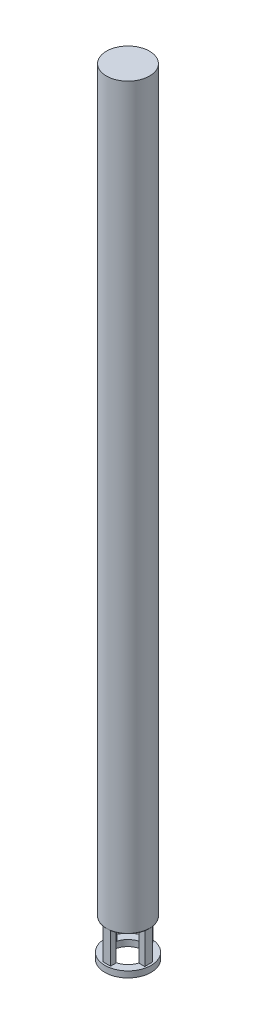
SolidWorks part; units mm, degrees
ref_plane "Plan de face" through (0, 0, 0) normal (0, 0, 1) x (1, 0, 0)
ref_plane "Plan de dessus" through (0, 0, 0) normal (0, 1, 0) x (1, 0, 0)
ref_plane "Plan de droite" through (0, 0, 0) normal (1, 0, 0) x (0, 0, -1)
sketch "Esquisse1" plane through (0, 0, 0) normal (0, 0, 1) x (1, 0, 0)
  line L0 (0, 0) -> (0, 90.4874) construction
  line L2 (0, 120) -> (-3.5, 120)
  line L3 (0, 120) -> (0, 0)
  line L4 (0, 0) -> (-3.5, 0)
  line L5 (-3.5, 120) -> (-3.5, 0)
  dimension "D1" = 120
  dimension "D2" = 3.5
revolve "Révolution1" add sketch "Esquisse1" angle 360 about L0
sketch "Esquisse6" plane through (0, 0, 0) normal (0, 1, 0) x (1, 0, 0)
  circle A1 centre (0, 0) radius 3.75
  circle A2 centre (0, 0) radius 2.5
  dimension "6" = 7.5
  dimension "D1" = 5
extrude "Boss.-Extru.2" add sketch "Esquisse6" along normal blind 1 from offset 6 offset against normal yes
sketch "Esquisse7" plane through (0, 0, 0) normal (0, 1, 0) x (1, 0, 0)
  line L1 (3.4, -0.675) -> (2.5, -0.675)
  line L2 (3.4, -0.675) -> (3.4, 0.575)
  line L3 (3.4, 0.575) -> (2.5, 0.575)
  line L4 (2.5, -0.675) -> (2.5, 0.575)
  dimension "D1" = 0.9
  dimension "D2" = 1.25
  dimension "D3" = 2.5
  dimension "D4" = 0.675
extrude "Boss.-Extru.3" add sketch "Esquisse7" against normal up to surface (5 mm away) up to face at (0, -5, 3.75)
sketch "Esquisse9" plane through (0, 0, 0) normal (1, 0, 0) x (0, 0, -1)
  line L0 (0, 0) -> (0, 33.7955) construction
pattern_circular "Répétition circulaire1" count 4 over 360 about axis through (0, 0, 0) along (0, 1, 0) of "Boss.-Extru.3"
fillet "Congé11" radius 0.1 1 edges at (0, 0, -3.5)
sketch "Esquisse10" plane through (0, 0, 0) normal (1, 0, 0) x (0, 0, -1)
  line L0 (3.5, 120) -> (-3.5, 120) construction
  circle A0 centre (0, 104) radius 1.5
  dimension "D1" = 3
  dimension "D2" = 16
extrude "Enlèv. mat.-Extru.1" cut sketch "Esquisse10" against normal blind 10 from offset 1 offset against normal yes
sketch "Esquisse11" plane through (0, 0, 0) normal (0, 1, 0) x (1, 0, 0)
  circle A0 centre (0, 0) radius 3.5
  circle A1 centre (0, 0) radius 2.75
  dimension "D1" = 5.5
  dimension "7" = 7
